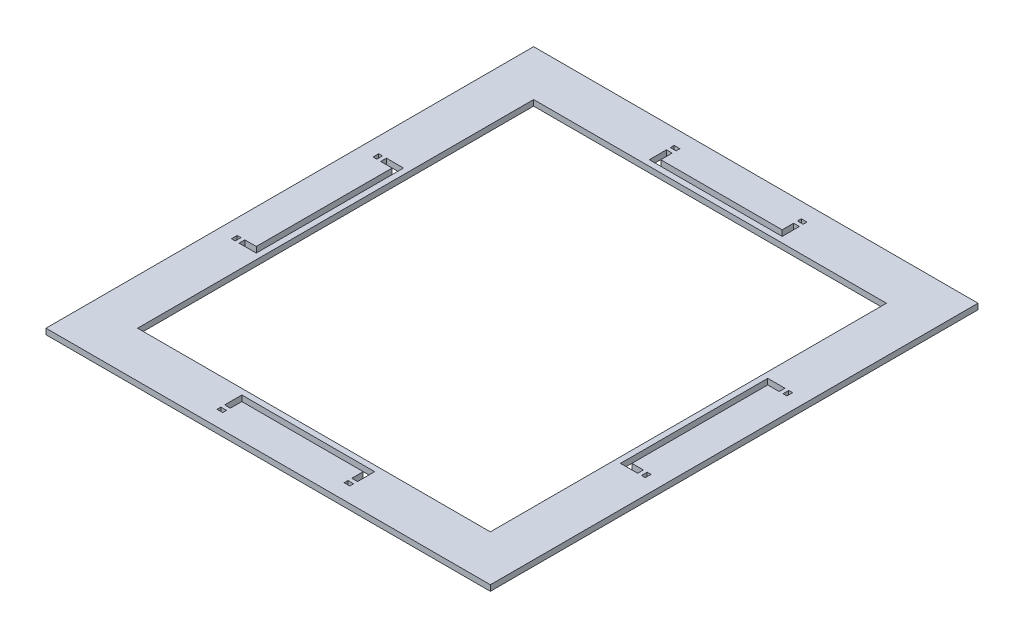
SolidWorks part; units mm, degrees
material "Delrin 2700 NC010, Low Viscosity Acetal Copolymer (SS)"
ref_plane "Front Plane" through (0, 0, 0) normal (0, 0, 1) x (1, 0, 0)
ref_plane "Top Plane" through (0, 0, 0) normal (0, 1, 0) x (1, 0, 0)
ref_plane "Right Plane" through (0, 0, 0) normal (1, 0, 0) x (0, 0, -1)
sketch "Sketch1" plane through (0, 0, 0) normal (0, 1, 0) x (1, 0, 0)
  line L0 (0, 135.225) -> (0, 0)
  line L1 (-110.525, 122.525) -> (0, 122.525)
  line L2 (-36.8417, 126.7583) -> (-33.6667, 126.7583)
  line L3 (-123.225, 135.225) -> (0, 135.225)
  line L4 (-123.225, 135.225) -> (-123.225, 0)
  line L5 (-36.8417, 126.7583) -> (-36.8417, 124.6417)
  line L6 (-36.8417, 124.6417) -> (-33.6667, 124.6417)
  line L7 (-33.6667, 126.7583) -> (-33.6667, 124.6417)
  line L8 (-114.7583, 40.8417) -> (-112.6417, 40.8417)
  line L9 (-114.7583, 40.8417) -> (-114.7583, 37.6667)
  line L10 (-114.7583, 37.6667) -> (-112.6417, 37.6667)
  line L11 (-112.6417, 40.8417) -> (-112.6417, 37.6667)
  line L12 (-110.525, 0) -> (-110.525, 122.525)
  line L13 (-110.525, 0) -> (-104.175, 0)
  line L14 (-110.525, 0) -> (-110.525, 37.6667)
  line L15 (-110.525, 37.6667) -> (-104.175, 37.6667)
  line L16 (-104.175, 0) -> (-104.175, 37.6667)
  line L17 (-110.525, 40.8417) -> (-101, 40.8417)
  line L18 (-110.525, 40.8417) -> (-110.525, 122.525)
  line L19 (-110.525, 122.525) -> (-78.9277, 122.525)
  line L20 (-101, 40.8417) -> (-101, 113)
  line L21 (-36.8417, 122.525) -> (-78.9277, 122.525)
  line L22 (-36.8417, 122.525) -> (-36.8417, 113)
  line L23 (-36.8417, 113) -> (-101, 113)
  line L24 (0, 122.525) -> (-33.6667, 122.525)
  line L25 (0, 122.525) -> (0, 116.175)
  line L26 (0, 116.175) -> (-33.6667, 116.175)
  line L27 (-33.6667, 122.525) -> (-33.6667, 116.175)
  line L28 (0, 0) -> (-123.225, 0)
  point P12 (0, 122.525)
  dimension "D1" = 12.7
  dimension "D2" = 2.1167
  dimension "D3" = 3.175
  dimension "D4" = 2.1167
  dimension "D5" = 2.1167
  dimension "D6" = 3.175
  dimension "D7" = 9.525
  dimension "D8" = 0
  dimension "D9" = 0
  dimension "D10" = 0
  dimension "D11" = 6.35
  dimension "D12" = 0
  dimension "D13" = 9.525
  dimension "D14" = 12.7
  dimension "D15" = 2.1167
  dimension "D16" = 6.35
  dimension "D17" = 104.175
  dimension "D18" = 67.3333
  dimension "D19" = 75.3333
  dimension "D21" = 116.175
extrude "Boss-Extrude1" add sketch "Sketch1" along normal blind 3.175 contours L28 L12 L1 L0 L3 L4 L8 L11 L10 L9 L2 L7 L6 L5 | L13 L16 L15 L12 | L23 L22 L1 L12 L17 L20 | L1 L27 L26 L0
sketch "Sketch3" plane through (0, 3.175, 0) normal (0, 1, 0) x (1, 0, 0)
  line L0 (0, 135.225) -> (0, 116.175) construction
  line L1 (-101, 113) -> (0, 113)
  line L2 (-101, 113) -> (-101, 109.825)
  line L3 (-101, 109.825) -> (0, 109.825)
  line L4 (0, 113) -> (0, 109.825)
  line L5 (-101, 113) -> (-97.825, 113)
  line L6 (-101, 113) -> (-101, 0)
  line L7 (-101, 0) -> (-97.825, 0)
  line L8 (-97.825, 113) -> (-97.825, 0)
  dimension "D1" = 3.175
  dimension "D2" = 3.175
  dimension "D3" = 0
  dimension "D4" = 0
extrude "Boss-Extrude2" add sketch "Sketch3" against normal blind 3.175 contours L5 L8 L7 L6 | L1 L4 L3 L2
mirror "Mirror4" about plane through (0, 0, 0) normal (1, 0, 0) of "Boss-Extrude2", "Boss-Extrude1"
mirror "Mirror5" about plane through (0, 0, 0) normal (0, 0, 1) of "Mirror4", "Boss-Extrude1", "Boss-Extrude2"
equation "\"D4@Sketch1\"=\"D2@Sketch1\""
equation "\"D15@Sketch1\"=\"D2@Sketch1\""
equation "\"D5@Sketch1\"=\"D2@Sketch1\""
equation "\"D6@Sketch1\"=\"D3@Sketch1\""
equation "\"D16@Sketch1\"=\"D11@Sketch1\""
equation "\"D13@Sketch1\"=\"D7@Sketch1\""
equation "\"Resolution Projector X\"= 1920'a_ resolution data"
equation "\"Resolution Projector Y\"= 1080'a_ resolution data"
equation "\"Resolution Build\"= 0.1'a_ resolution data"
equation "\"Size Build Volume X\"= \"Resolution Projector X\" * \"Resolution Build\"'b_ build volume data"
equation "\"Size Build Volume Y\"= 2 * \"Resolution Projector Y\" * \"Resolution Build\"'b_ build volume data"
equation "\"Size Build Volume Z\"= \"Size Build Volume Y\"'b_ build volume data"
equation "\"Size Enclosure Internal X\"= 350mm'c_ size enclosure Internal data"
equation "\"Size Enclosure Internal Y\"= \"Size Enclosure Internal X\"'c_ size enclosure Internal data"
equation "\"Size Enclosure Internal Z\"= \"Size Enclosure Internal X\"'c_ size enclosure Internal data"
equation "\"Size Enclosure External Z\"= 1000mm'c_ size enclosure External data"
equation "\"Clearance Vat\"= 10mm'd_ clearance vat data"
equation "\"Size Vat X\"= \"Size Build Volume X\" + \"Clearance Vat\"'f_ size vat data"
equation "\"Size Vat Y\"= \"Size Build Volume Y\" + \"Clearance Vat\"'f_ size vat data"
equation "\"Size Vat Z\"= \"Size Build Volume Z\" + \"Clearance Vat\"'f_ size vat data"
equation "\"Thickness Vat\"= 3.175mm'g_ thickness vat data"
equation "\"width rib\"= 2 * \"Thickness Vat\"'g_ thickness of the Rib"
equation "\"width Lip on rib\"= \"Thickness Vat\" * 2'g_ thickness of the lip connected to the tab"
equation "\"height Lip on rib\" = \"width Lip on rib\"'g_ height of lip on rib structure"
equation "\"height adjustment\" = \"Thickness Vat\" * 2'g_ height adjustment for lip.  This flushes the top part of the tab to top of the walls"
equation "\"goofy tab x\"= \"Size Vat X\" * ( 1 / 3 ) - \"width rib\"'h_ goofy slot found on rib X"
equation "\"goofy tab y\"= \"Size Vat Y\" * ( 1 / 3 ) - \"width rib\"'h_ goofy slot found on rib Y"
equation "\"D3@Sketch1\"=\"Thickness Vat\""
equation "\"D18@Sketch1\"=\"Size Vat X\"/3"
equation "\"D19@Sketch1\"=\"Size Vat Y\"/3"
equation "\"D1@Sketch1\"=\"width Lip on rib\"*2mm"
equation "\"D14@Sketch1\"=\"D1@Sketch1\""
equation "\"D11@Sketch1\"=\"Thickness Vat\"*2"
equation "\"D7@Sketch1\"=\"Thickness Vat\"*3"
equation "\"D17@Sketch1\"=\"Size Vat X\"/2 + \"Thickness Vat\""
equation "\"D21@Sketch1\"=\"Size Vat Y\"/2 + \"Thickness Vat\""
equation "\"D1@Boss-Extrude1\"=\"Thickness Vat\""
equation "\"D1@Sketch3\"=\"Thickness Vat\""
equation "\"D2@Sketch3\"=\"Thickness Vat\""
equation "\"D1@Boss-Extrude2\"=\"Thickness Vat\""
